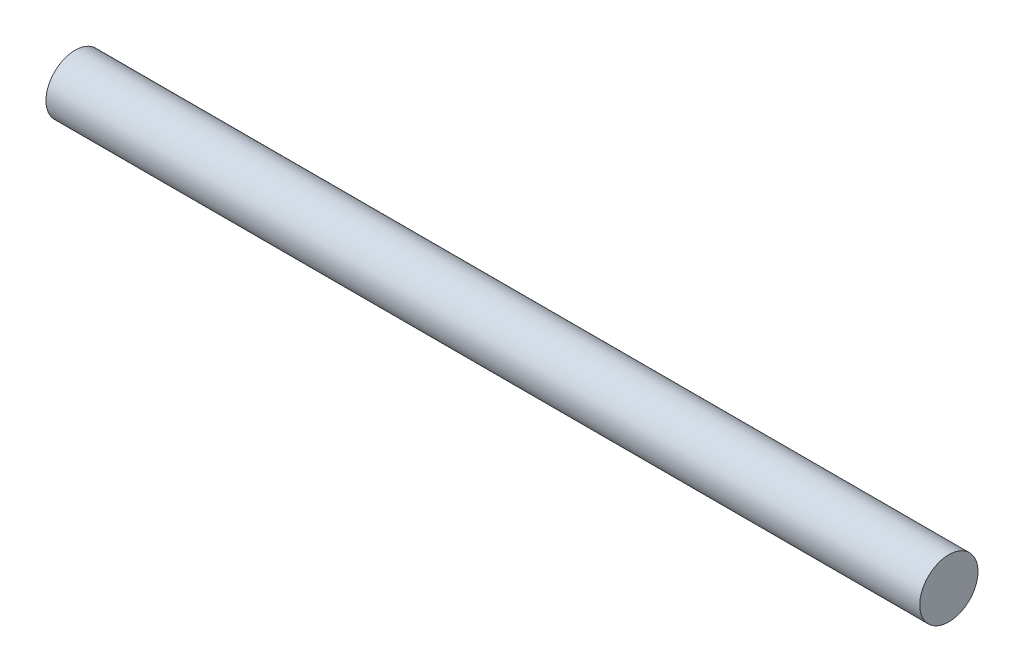
SolidWorks part; units mm, degrees
ref_plane "Front Plane" through (0, 0, 0) normal (1, 0, 0) x (0, 1, 0)
ref_plane "Top Plane" through (0, 0, 0) normal (0, 0, 1) x (0, 1, 0)
ref_plane "Right Plane" through (0, 0, 0) normal (0, 1, 0) x (-1, 0, 0)
sketch "Sketch2" plane through (0, 0, 0) normal (1, 0, 0) x (0, 1, 0)
  circle A0 centre (0, 0) radius 5
  dimension "D1" = 10
extrude "Boss-Extrude1" add sketch "Sketch2" along normal mid plane 150
